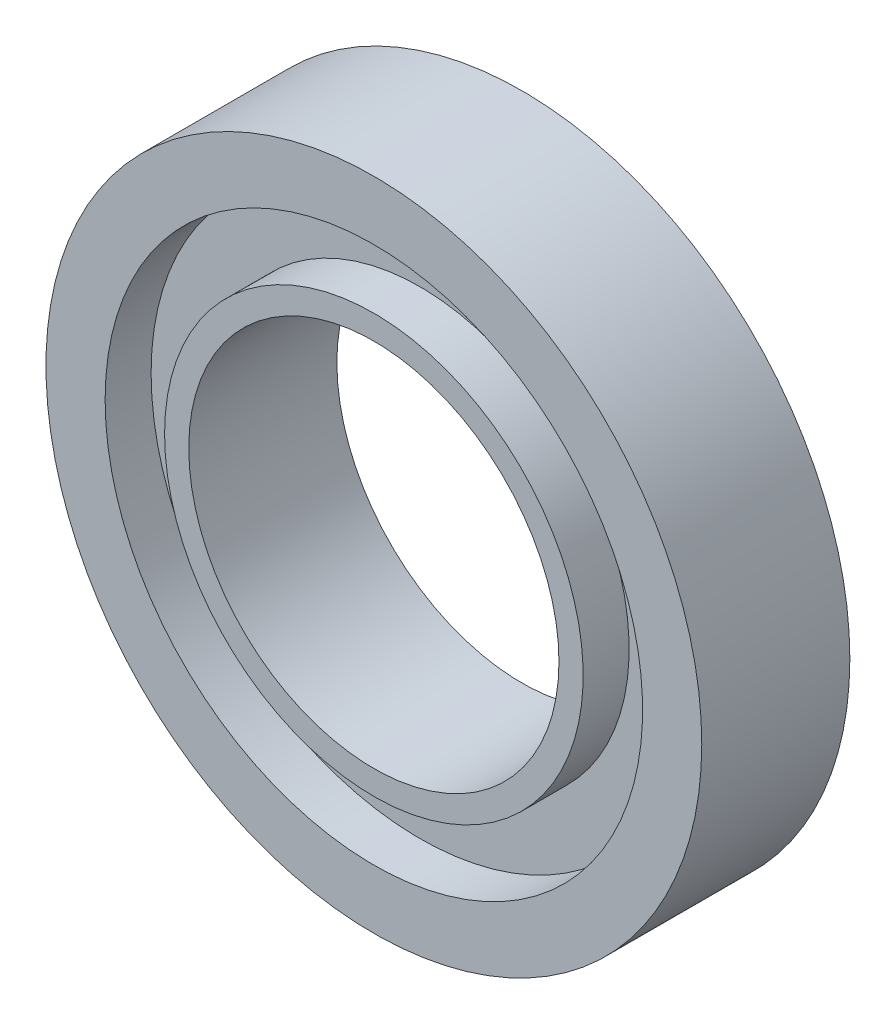
SolidWorks part; units mm, degrees
ref_plane "前视基准面" through (0, 0, 0) normal (0, 0, 1) x (1, 0, 0)
ref_plane "上视基准面" through (0, 0, 0) normal (0, 1, 0) x (1, 0, 0)
ref_plane "右视基准面" through (0, 0, 0) normal (1, 0, 0) x (0, 0, -1)
other "Configuration Table"
sketch "草图1" plane through (0, 0, 0) normal (0, 0, 1) x (1, 0, 0)
  circle A0 centre (0, 0) radius 17.5
  circle A1 centre (0, 0) radius 31
  dimension "D1" = 35
  dimension "D2" = 62
extrude "凸台-拉伸1" add sketch "草图1" along normal mid plane 14
sketch "草图2" plane through (0, 0, 0) normal (0, 1, 0) x (1, 0, 0)
  line L0 (0, 7) -> (0, -7)
  line L1 (31, 7) -> (-31, 7) construction
  line L2 (-31, -7) -> (31, -7) construction
  line L3 (19.7859, 7) -> (19.7859, 2.6531)
  line L4 (19.7859, 2.6531) -> (25.4069, 2.6531)
  line L5 (25.4069, 2.6531) -> (25.4069, 7)
  line L6 (25.4069, 7) -> (19.7859, 7)
revolve "切除-旋转1" cut sketch "草图2" angle 360 about L0
mirror "镜向1" about plane through (0, 0, 0) normal (0, 0, 1) of "切除-旋转1"
